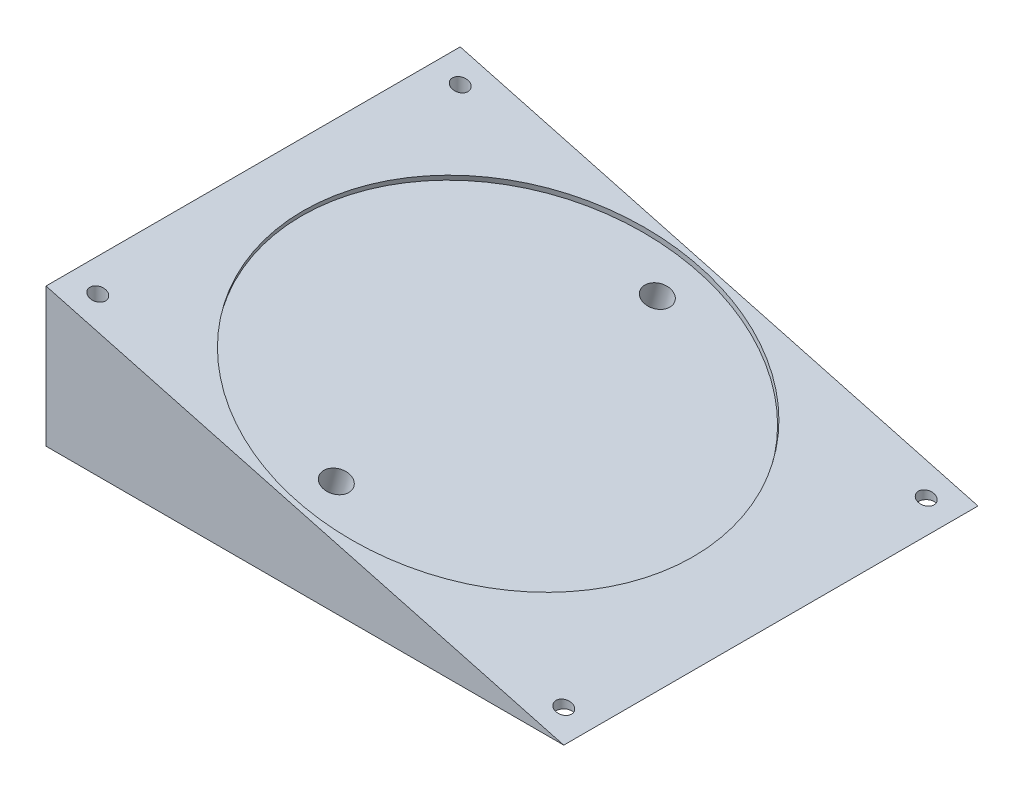
SolidWorks part; units mm, degrees
ref_plane "Alzado" through (0, 0, 0) normal (0, 0, 1) x (1, 0, 0)
ref_plane "Planta" through (0, 0, 0) normal (0, 1, 0) x (1, 0, 0)
ref_plane "Vista lateral" through (0, 0, 0) normal (1, 0, 0) x (0, 0, -1)
sketch "Croquis1" plane through (0, 0, 0) normal (0, 0, 1) x (1, 0, 0)
  line L0 (-50, 0) -> (50, 0)
  line L1 (0, 0) -> (0, 38.3533) construction
  line L2 (50, 0) -> (-50, 26.7949)
  line L3 (-50, 26.7949) -> (-50, 0)
  dimension "D1" = 50
  dimension "D2" = 15
extrude "Saliente-Extruir1" add sketch "Croquis1" along normal blind 80
sketch "Croquis2" plane through (3.3494, 12.5, 0) normal (0.2588, 0.9659, 0) x (0.9659, -0.2588, 0)
  circle A2 centre (-6.2313, -40) radius 39
extrude "Cortar-Extruir1" cut sketch "Croquis2" against normal blind 1 contours A2
sketch "Croquis3" plane through (3.0905, 11.5341, 0) normal (0.2588, 0.9659, 0) x (0.9659, -0.2588, 0)
  circle A3 centre (-6.2313, -9) radius 2.5
  circle A4 centre (-6.2313, -71) radius 2.5
extrude "Cortar-Extruir2" cut sketch "Croquis3" against normal blind 6 contours A3 | A4
sketch "Croquis5" plane through (0, 0, 0) normal (0, -1, 0) x (1, 0, 0)
  line L0 (0, 40) -> (0, 81.3513) construction
  line L1 (0, 40) -> (62.2872, 40) construction
  circle A1 centre (-45, 75) radius 1.5
  circle A2 centre (45, 75) radius 1.5
  circle A3 centre (45, 5) radius 1.5
  circle A4 centre (-45, 5) radius 1.5
  point P8 (0, 40)
  dimension "D1" = 70
  dimension "D2" = 90
extrude "Cortar-Extruir3" cut sketch "Croquis5" against normal blind 40 contours A1 | A2 | A3 | A4
